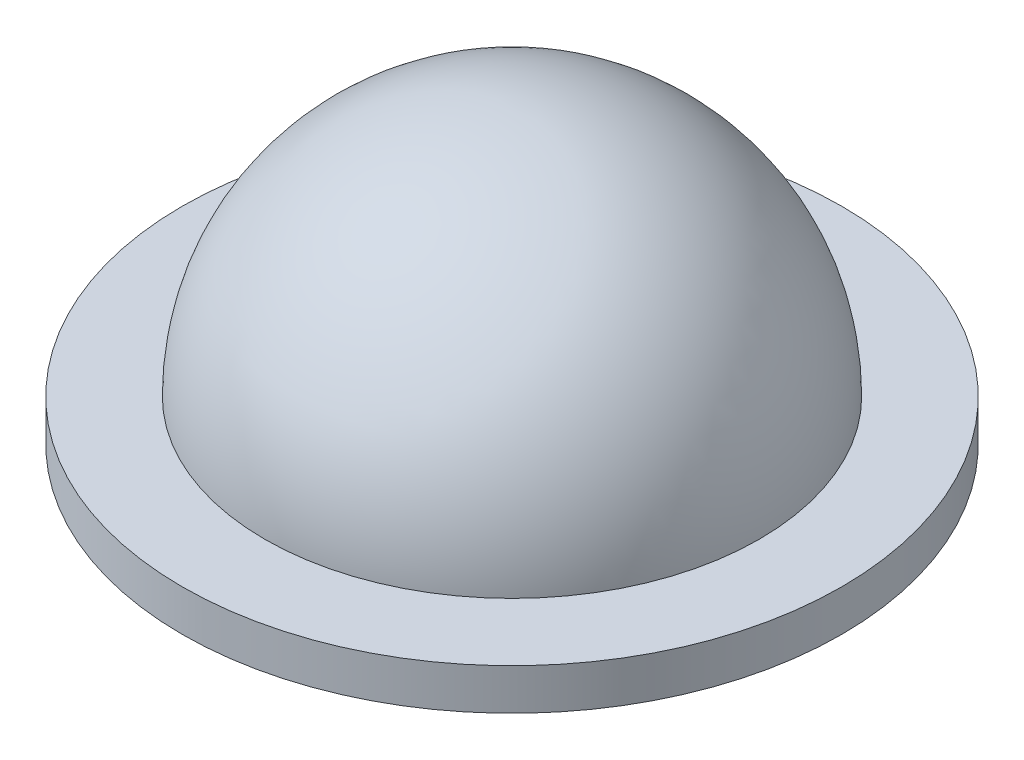
SolidWorks part; units mm, degrees
ref_plane "Front Plane" through (0, 0, 0) normal (0, 0, 1) x (1, 0, 0)
ref_plane "Top Plane" through (0, 0, 0) normal (0, 1, 0) x (1, 0, 0)
ref_plane "Right Plane" through (0, 0, 0) normal (1, 0, 0) x (0, 0, -1)
sketch "Sketch1" plane through (0, 0, 0) normal (0, 0, 1) x (1, 0, 0)
  line L0 (0, 0) -> (-3.101, 0)
  line L1 (-3.101, 0) -> (-3.101, 1)
  line L2 (-3.101, 1) -> (-1.101, 1)
  line L3 (4.899, 7) -> (4.899, 6)
  arc A0 (-1.101, 1) -> (4.899, 7) centre (4.899, 1) cw
  arc A1 (4.899, 6) -> (0, 0) centre (4.899, 1) ccw
  dimension "D4" = 6
  dimension "D5" = 5
  dimension "D1" = 1
  dimension "D2" = 2
  dimension "D3" = 1
revolve "Revolve1" add sketch "Sketch1" angle 360 about L3
